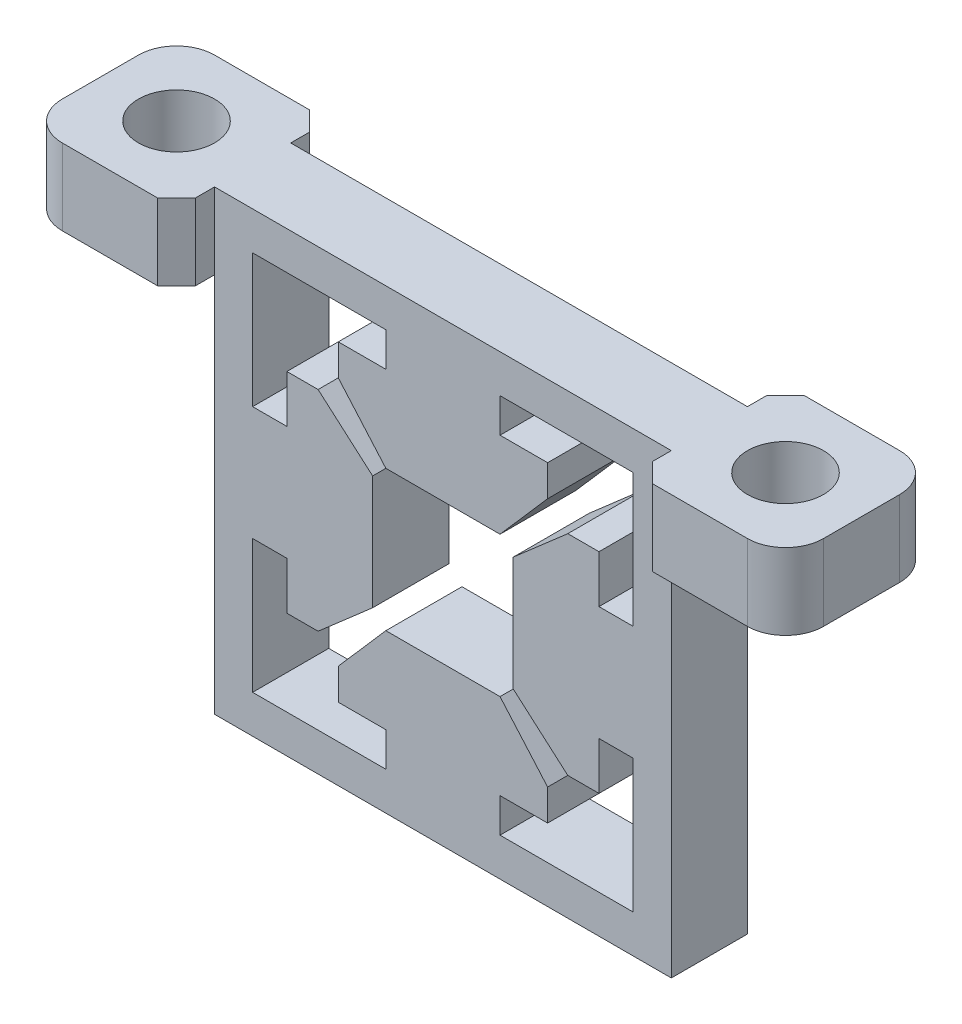
SolidWorks part; units mm, degrees
ref_plane "Спереди" through (0, 0, 0) normal (0, 0, 1) x (1, 0, 0)
ref_plane "Сверху" through (0, 0, 0) normal (0, 1, 0) x (1, 0, 0)
ref_plane "Справа" through (0, 0, 0) normal (1, 0, 0) x (0, 0, -1)
other "Configuration Table"
sketch "Эскиз1" plane through (0, 0, 0) normal (0, 0, 1) x (1, 0, 0)
  line L0 (0, 10) -> (3, 10)
  line L1 (-10, -10) -> (10, -10)
  line L2 (-10, -10) -> (-10, 10)
  line L3 (-10, 10) -> (10, 10)
  line L4 (10, -10) -> (10, 10)
  line L5 (0, 10) -> (-3, 10)
  line L6 (-3, 10) -> (-3, 8.2)
  line L7 (3, 10) -> (3, 8.2)
  line L8 (0, 10) -> (-5.5, 10)
  line L9 (0, 10) -> (5.5, 10)
  line L10 (-3, 8.2) -> (-5.5, 8.2)
  line L11 (3, 8.2) -> (5.5, 8.2)
  line L12 (-5.5, 8.2) -> (-5.5, 6.56)
  line L13 (5.5, 8.2) -> (5.5, 6.56)
  line L14 (-3, 3.694) -> (3, 3.694)
  line L15 (5.5, 8.2) -> (5.5, 6.56)
  line L16 (-5.5, 8.2) -> (-5.5, 6.56)
  line L17 (-3, 3.694) -> (-5.5, 6.56)
  line L18 (3, 3.694) -> (5.5, 6.56)
  line L19 (-10, 0) -> (10, 0) construction
  line L20 (-10, -3) -> (-8.2, -3)
  line L21 (-10, 3) -> (-8.2, 3)
  line L22 (-8.2, -3) -> (-8.2, -5.5)
  line L23 (-8.2, 3) -> (-8.2, 5.5)
  line L24 (-8.2, -5.5) -> (-6.56, -5.5)
  line L25 (-8.2, 5.5) -> (-6.56, 5.5)
  line L26 (-3.694, -3) -> (-3.694, 3)
  line L27 (-3.694, -3) -> (-6.56, -5.5)
  line L28 (-3.694, 3) -> (-6.56, 5.5)
  line L29 (0, 10) -> (0, -10) construction
  line L30 (10, 3) -> (8.2, 3)
  line L31 (10, -3) -> (8.2, -3)
  line L32 (8.2, 3) -> (8.2, 5.5)
  line L33 (8.2, -3) -> (8.2, -5.5)
  line L34 (8.2, 5.5) -> (6.56, 5.5)
  line L35 (8.2, -5.5) -> (6.56, -5.5)
  line L36 (3.694, 3) -> (3.694, -3)
  line L37 (3.694, 3) -> (6.56, 5.5)
  line L38 (3.694, -3) -> (6.56, -5.5)
  line L39 (3, -10) -> (3, -8.2)
  line L40 (-3, -10) -> (-3, -8.2)
  line L41 (3, -8.2) -> (5.5, -8.2)
  line L42 (-3, -8.2) -> (-5.5, -8.2)
  line L43 (5.5, -8.2) -> (5.5, -6.56)
  line L44 (-5.5, -8.2) -> (-5.5, -6.56)
  line L45 (3, -3.694) -> (-3, -3.694)
  line L46 (3, -3.694) -> (5.5, -6.56)
  line L47 (-3, -3.694) -> (-5.5, -6.56)
  line L48 (-12, -12) -> (12, -12)
  line L49 (12, -12) -> (12, 12)
  line L50 (-12, -12) -> (-12, 12)
  line L51 (-12, 12) -> (12, 12)
  point P34 (0, 0)
  dimension "D1" = 20
  dimension "D2" = 20
  dimension "D3" = 3
  dimension "D4" = 3
  dimension "D5" = 1.8
  dimension "D6" = 1.8
  dimension "D7" = 5.5
  dimension "D8" = 5.5
  dimension "D9" = 2.5
  dimension "D10" = 2.5
  dimension "D11" = 3
  dimension "D12" = 1.8
  dimension "D13" = 1.64
  dimension "D14" = 1.64
  dimension "D15" = 3.8032
  dimension "D16" = 3.8032
  dimension "D17" = 6
  dimension "D18" = 1.64
  dimension "D19" = 3.0806
  dimension "D20" = 4.506
  dimension "D21" = 6
  dimension "D22" = 1.8
  dimension "D23" = 1.64
  dimension "D24" = 3.8032
  dimension "D25" = 3
  dimension "D26" = 3
  dimension "D27" = 2
  dimension "D28" = 24
  dimension "D29" = 24
  dimension "D30" = 24
  dimension "D31" = 2
extrude "Бобышка-Вытянуть1" add sketch "Эскиз1" along normal blind 4 contours L45 L47 L44 L42 L40 L1 L39 L41 L43 L46 | L51 L50 L48 L49 L4 L1 L2 L3 L0 | L36 L38 L35 L33 L31 L4 L30 L32 L34 L37 | L26 L28 L25 L23 L21 L2 L20 L22 L24 L27 | L14 L18 L13 L11 L7 L0 L3 L6 L10 L12 L17
sketch "Эскиз6" plane through (0, 12, 0) normal (0, 1, 0) x (1, 0, 0)
  line L1 (-12, 2) -> (-18, 2)
  line L2 (-12, 2) -> (-12, -6)
  line L3 (-12, -6) -> (-18, -6)
  line L4 (-20, 0) -> (-20, -4)
  line L9 (-12, -2) -> (-38.0803, -2) construction
  line L10 (-12, -4) -> (-12, 0) construction
  arc A0 (-18, 2) -> (-20, 0) centre (-18, 0) ccw
  arc A1 (-20, -4) -> (-18, -6) centre (-18, -4) ccw
  circle A2 centre (-16, -2) radius 2
  point P8 (-12, -2)
  point P11 (-20, 2)
  point P14 (-20, -6)
  dimension "D3" = 2
  dimension "D4" = 2
  dimension "D5" = 4
  dimension "D1" = 8
  dimension "D2" = 8
  dimension "D6" = 4
extrude "Бобышка-Вытянуть2" add sketch "Эскиз6" against normal blind 4
chamfer "Фаска1" distance 1 angle 45 2 edges at (-12, 10, -2) (-12, 10, 6)
mirror "Зеркальное отражение1" about plane through (0, 0, 0) normal (1, 0, 0) of "Фаска1", "Бобышка-Вытянуть2"
